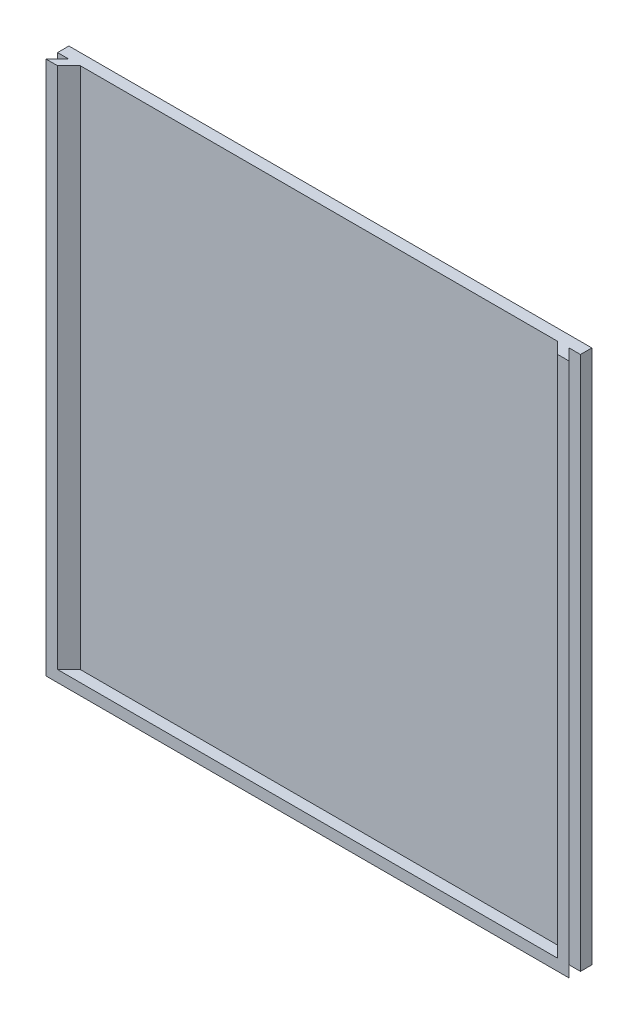
SolidWorks part; units mm, degrees
ref_plane "前视基准面" through (0, 0, 0) normal (0, 0, 1) x (1, 0, 0)
ref_plane "上视基准面" through (0, 0, 0) normal (0, 1, 0) x (1, 0, 0)
ref_plane "右视基准面" through (0, 0, 0) normal (1, 0, 0) x (0, 0, -1)
other "Configuration Table"
sketch "草图1" plane through (0, 0, 0) normal (0, 1, 0) x (1, 0, 0)
  line L0 (23, 2.1) -> (23, 1.1)
  line L1 (23, 1.1) -> (22, 1.1)
  line L2 (22, 1.1) -> (23, 0.1)
  line L3 (23, 0.1) -> (22, 0.1)
  line L4 (21, 1.1) -> (22, 0.1)
  line L5 (-21, 1.1) -> (-22, 0.1)
  line L6 (-23, 0.1) -> (-22, 0.1)
  line L7 (-22, 1.1) -> (-23, 0.1)
  line L8 (-23, 2.1) -> (-23, 1.1)
  line L9 (21, 1.1) -> (-21, 1.1)
  line L10 (-22, 1.1) -> (-23, 1.1)
  line L11 (-23, 2.1) -> (23, 2.1)
  line L12 (23.1, 2.2) -> (23.1, 1)
  line L13 (23.1, 1) -> (22.2414, 1)
  line L14 (22.2414, 1) -> (23.2414, 0)
  line L15 (23.2414, 0) -> (21.9586, 0)
  line L16 (22, 0.1) -> (-22, 0.1)
  line L19 (-23.2414, 0) -> (-21.9586, 0)
  line L20 (-22.2414, 1) -> (-23.2414, 0)
  line L21 (-22.2414, 1) -> (-23.1, 1)
  line L22 (-23.1, 2.2) -> (-23.1, 1)
  line L23 (-23.1, 2.2) -> (23.1, 2.2)
  point P3 (0, -0.1405)
  point P13 (0, -0.1405)
  dimension "D1" = 1
  dimension "D2" = 1
  dimension "D3" = 1
  dimension "D4" = 1
  dimension "D5" = 1
  dimension "D6" = 1
  dimension "D7" = 1
  dimension "D8" = 45
  dimension "D9" = 45
  dimension "D10" = 1
extrude "凸台-拉伸1" add sketch "草图1" along normal blind 47 contours L11 L8 L10 L7 L6 L5 L9 L4 L3 L2 L1 L0
sketch "草图2" plane through (0, 0, 0) normal (0, -1, 0) x (1, 0, 0)
  line L0 (21, -1.1) -> (22, -0.1) construction
  line L1 (21, -1.1) -> (-21, -1.1) construction
  line L2 (-21, -1.1) -> (-22, -0.1) construction
  line L3 (23, -0.1) -> (22, -0.1) construction
  line L4 (22, -1.1) -> (23, -0.1) construction
  line L5 (23, -1.1) -> (22, -1.1) construction
  line L6 (23, -2.1) -> (23, -1.1) construction
  line L7 (-23, -2.1) -> (23, -2.1) construction
  line L8 (-23, -2.1) -> (-23, -1.1) construction
  line L9 (-22, -1.1) -> (-23, -1.1) construction
  line L10 (-22, -1.1) -> (-23, -0.1) construction
  line L11 (-23, -0.1) -> (-22, -0.1) construction
  line L12 (22, -0.1) -> (-22, -0.1) construction
  line L13 (-23.2414, 0) -> (-21.9586, 0) construction
  line L14 (-22.2414, -1) -> (-23.2414, 0) construction
  line L15 (-22.2414, -1) -> (-23.1, -1) construction
  line L16 (-23.1, -2.2) -> (-23.1, -1) construction
  line L17 (-23.1, -2.2) -> (23.1, -2.2) construction
  line L18 (23.1, -2.2) -> (23.1, -1) construction
  line L19 (23.1, -1) -> (22.2414, -1) construction
  line L20 (22.2414, -1) -> (23.2414, 0) construction
  line L21 (23.2414, 0) -> (21.9586, 0) construction
  line L22 (21, -1.1) -> (22, -0.1)
  line L23 (21, -1.1) -> (-21, -1.1)
  line L24 (-21, -1.1) -> (-22, -0.1)
  line L25 (23, -0.1) -> (22, -0.1)
  line L26 (22, -1.1) -> (23, -0.1)
  line L27 (23, -1.1) -> (22, -1.1)
  line L28 (23, -2.1) -> (23, -1.1)
  line L29 (-23, -2.1) -> (23, -2.1)
  line L30 (-23, -2.1) -> (-23, -1.1)
  line L31 (-22, -1.1) -> (-23, -1.1)
  line L32 (-22, -1.1) -> (-23, -0.1)
  line L33 (-23, -0.1) -> (-22, -0.1)
  line L34 (22, -0.1) -> (-22, -0.1)
  line L35 (-23.2414, 0) -> (-21.9586, 0)
  line L36 (-22.2414, -1) -> (-23.2414, 0)
  line L37 (-22.2414, -1) -> (-23.1, -1)
  line L38 (-23.1, -2.2) -> (-23.1, -1)
  line L39 (-23.1, -2.2) -> (23.1, -2.2)
  line L40 (23.1, -2.2) -> (23.1, -1)
  line L41 (23.1, -1) -> (22.2414, -1)
  line L42 (22.2414, -1) -> (23.2414, 0)
  line L43 (23.2414, 0) -> (21.9586, 0)
  line M6 (22, -0.1) -> (21, -1.1)
  line M7 (21, -1.1) -> (-21, -1.1)
  line M8 (-21, -1.1) -> (-22, -0.1)
extrude "凸台-拉伸3" add sketch "草图2" against normal blind 1 contours L34 M6 M8 M7
